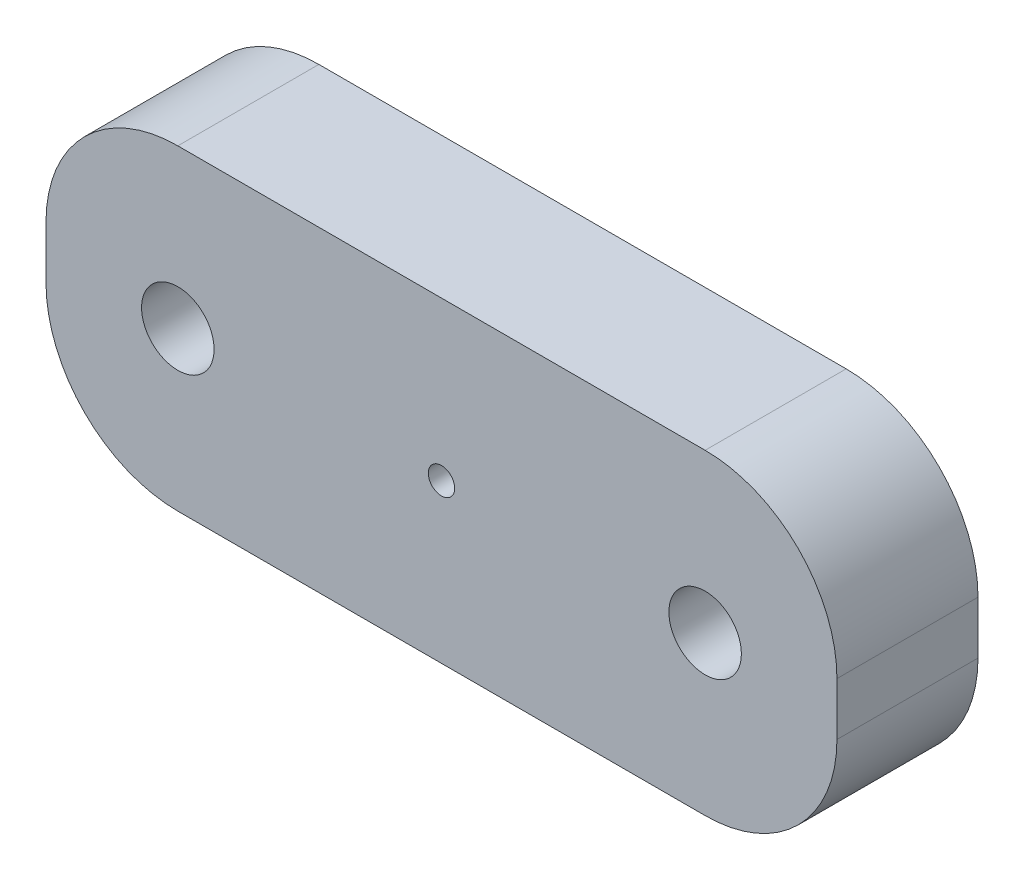
SolidWorks part; units mm, degrees
ref_plane "Front Plane" through (0, 0, 0) normal (0, 0, 1) x (1, 0, 0)
ref_plane "Top Plane" through (0, 0, 0) normal (0, 1, 0) x (1, 0, 0)
ref_plane "Right Plane" through (0, 0, 0) normal (1, 0, 0) x (0, 0, -1)
sketch "Model" plane through (0, 0, 0) normal (0, 0, 1) x (1, 0, 0)
  line L0 (-15, 6) -> (15, 6) construction
  line L1 (-10, 0) -> (10, 0)
  line L2 (-15, 5) -> (-15, 7)
  line L3 (-10, 12) -> (10, 12)
  line L4 (15, 5) -> (15, 7)
  line L5 (-10, 12) -> (-10, 0) construction
  line L6 (0, 0) -> (0, 12) construction
  arc A0 (-15, 5) -> (-10, 0) centre (-10, 5) ccw
  arc A1 (-10, 12) -> (-15, 7) centre (-10, 7) ccw
  arc A2 (15, 7) -> (10, 12) centre (10, 7) ccw
  arc A3 (10, 0) -> (15, 5) centre (10, 5) ccw
  circle A4 centre (-10, 6) radius 1.2
  circle A5 centre (-10, 6) radius 1.375
  circle A6 centre (10, 6) radius 1.375
  circle A7 centre (10, 6) radius 1.2
  circle A8 centre (0, 6) radius 0.5
  dimension "D1" = 5
  dimension "D11" = 2.4
  dimension "D15" = 0.175
  dimension "D17" = 1
  dimension "D12" = 20
  dimension "D14" = 12
extrude "Boss-Extrude1" add sketch "Model" along normal blind 5.35 contours L1 A3 L4 A2 L3 A1 L2 A0 A8 A5 A6
equation "\"mdfthick\"=5.35"
equation "\"D1@Boss-Extrude1\"=\"mdfthick\""
